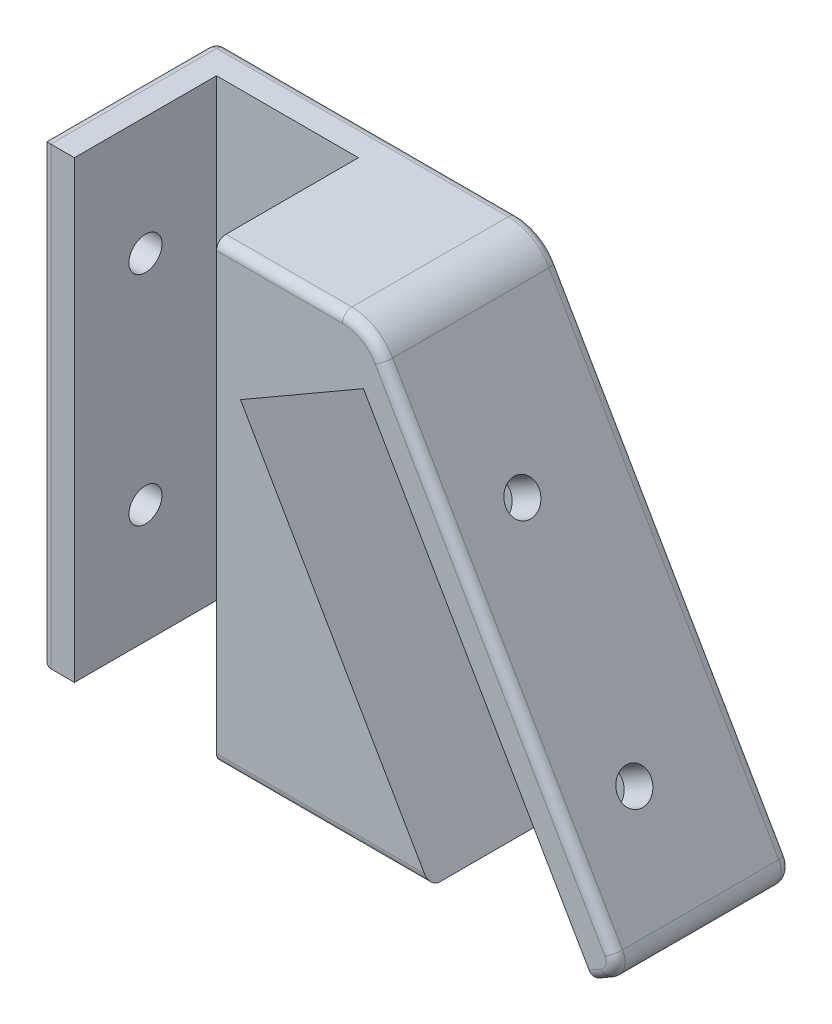
SolidWorks part; units mm, degrees
ref_plane "Front Plane" through (0, 0, 0) normal (0, 0, 1) x (1, 0, 0)
ref_plane "Top Plane" through (0, 0, 0) normal (0, 1, 0) x (1, 0, 0)
ref_plane "Right Plane" through (0, 0, 0) normal (1, 0, 0) x (0, 0, -1)
sketch "Sketch1" plane through (0, 0, 0) normal (0, 0, 1) x (1, 0, 0)
  line L0 (20.5456, 15.4888) -> (48.2584, -32.5112)
  line L2 (-14.145, 15.4888) -> (-14.145, -32.5112)
  line L3 (-14.145, -32.5112) -> (7.855, -32.5112)
  line L4 (7.855, 37.4696) -> (7.855, -32.5112) construction
  line L5 (48.2584, -32.5112) -> (7.855, -32.5112)
  line L6 (22.855, -32.5112) -> (7.855, -6.5304) construction
  line L7 (7.855, -6.5304) -> (45.9934, 15.4888) construction
  line L8 (20.5456, 15.4888) -> (-14.145, 15.4888)
  dimension "D2" = 30
  dimension "D3" = 22
  dimension "D4" = 30
  dimension "D5" = 48
extrude "Boss-Extrude1" add sketch "Sketch1" along normal blind 18.5
sketch "Sketch2" plane through (0, 0, 18.5) normal (0, 0, 1) x (1, 0, 0)
  line L1 (-14.145, -32.5112) -> (48.2584, -32.5112) construction
  line L2 (-10.645, 15.4888) -> (4.355, 15.4888)
  line L3 (-10.645, 15.4888) -> (-10.645, -32.5112)
  line L4 (-10.645, -32.5112) -> (4.355, -32.5112)
  line L5 (4.355, 15.4888) -> (4.355, -32.5112)
  line L6 (-14.145, 15.4888) -> (-14.145, -32.5112) construction
  line L7 (44.2169, -32.5112) -> (19.8868, 9.6298)
  line L8 (19.8868, 9.6298) -> (6.8964, 2.1298)
  line L9 (6.8964, 2.1298) -> (26.8964, -32.5112)
  line L10 (26.8964, -32.5112) -> (44.2169, -32.5112)
  line L11 (48.2584, -32.5112) -> (20.5456, 15.4888) construction
  line L12 (20.5456, 15.4888) -> (-14.145, 15.4888) construction
  dimension "D1" = 15
  dimension "D2" = 3.5
  dimension "D3" = 3.5
  dimension "D4" = 15
  dimension "D5" = 40
extrude "Cut-Extrude1" cut sketch "Sketch2" against normal offset from surface (15 mm away) 3.5 up to face at (10.1285, -8.5112, 0)
sketch "Sketch3" plane through (22.116, 12.7687, 0) normal (0.866, 0.5, 0) x (0, 0, -1)
  line L0 (-11, 30.2721) -> (-11, -52.2847) construction
  line L1 (-3.5, -1.6038) -> (-18.5, -1.6038) construction
  line L2 (-18.5, -52.2847) -> (0, -52.2847) construction
  line L3 (-3.5, -50.264) -> (-18.5, -50.264) construction
  circle A0 centre (-11, -37.764) radius 1.75
  circle A2 centre (-11, -14.1038) radius 1.75
  dimension "D1" = 3.5
  dimension "D2" = 12.5
  dimension "D3" = 12.5
extrude "Cut-Extrude2" cut sketch "Sketch3" against normal blind 3.5
sketch "Sketch4" plane through (0, 0, 0) normal (0, 0, -1) x (-1, 0, 0)
  line L0 (3.145, 15.4888) -> (3.145, -32.5112) construction
  line L2 (14.145, -32.5112) -> (-48.2584, -32.5112) construction
  line L3 (-13.3916, 5.8798) -> (-35.5567, -32.5112) construction
  line L4 (-6.8964, 2.1298) -> (-19.8868, 9.6298) construction
  line L5 (10.645, 15.4888) -> (-4.355, 15.4888) construction
  circle A0 centre (-29.3067, -21.6859) radius 1.75
  circle A2 centre (-19.6416, -4.9455) radius 1.75
  circle A4 centre (3.145, 2.9888) radius 1.75
  circle A6 centre (3.145, -20.0112) radius 1.75
  circle A7 centre (3.145, 14.4888) radius 1.75 [skipped]
  circle A8 centre (3.145, -8.5112) radius 1.75 [skipped]
  point P2 (0, 0)
  dimension "D1" = 12.5
  dimension "D2" = 12.5
  dimension "D4" = 3.5
  dimension "D5" = 4
  dimension "D6" = 12.5
  dimension "D7" = 12.5
extrude "Cut-Extrude3" cut sketch "Sketch4" against normal blind 4
sketch "Sketch5" plane through (-14.145, 0, 0) normal (-1, 0, 0) x (0, 0, 1)
  line L0 (11, 15.4888) -> (11, -32.5112) construction
  line L2 (18.5, -32.5112) -> (0, -32.5112) construction
  line L3 (18.5, 15.4888) -> (18.5, -32.5112) construction
  line L4 (18.5, 15.4888) -> (0, 15.4888) construction
  circle A0 centre (11, -20.0112) radius 1.75
  circle A2 centre (11, 2.9888) radius 1.75
  circle A4 centre (11, 14.4888) radius 1.75 [skipped]
  circle A5 centre (11, -8.5112) radius 1.75 [skipped]
  dimension "D2" = 3.5
  dimension "D3" = 12.5
  dimension "D5" = 12.5
  dimension "D1" = 7.5
  dimension "D4" = 4
extrude "Cut-Extrude4" cut sketch "Sketch5" against normal blind 4
sketch "Sketch6" plane through (0, 0, 18.5) normal (0, 0, 1) x (1, 0, 0)
  line L0 (44.2169, -32.5112) -> (47.248, -30.7612)
  line L1 (48.2584, -32.5112) -> (20.5456, 15.4888) construction
  line L2 (47.248, -30.7612) -> (48.2584, -32.5112)
  line L3 (48.2584, -32.5112) -> (44.2169, -32.5112)
extrude "Cut-Extrude5" cut sketch "Sketch6" against normal blind 19
fillet "Fillet1" radius 2 1 edges at (47.248, -30.7612, 9.25)
fillet "Fillet2" radius 5 1 edges at (20.5456, 15.4888, 9.25)
fillet "Fillet3" radius 1 16 edges at (44.8665, -32.1362, 18.5) (46.4478, -30.5468, 18.5) (34.1185, -8.0202, 18.5) (20.1588, 14.8189, 18.5) (44.8665, -32.1362, 0) (46.4478, -30.5468, 0) (34.1185, -8.0202, 0) (20.1588, 14.8189, 0) (15.6257, -32.5112, 18.5) (11.0069, 15.4888, 18.5) (-14.145, -32.5112, 9.25) (-14.145, 15.4888, 9.25) (-14.145, -8.5112, 18.5) (15.036, -32.5112, 0) (1.7569, 15.4888, 0) (-14.145, -8.5112, 0)
